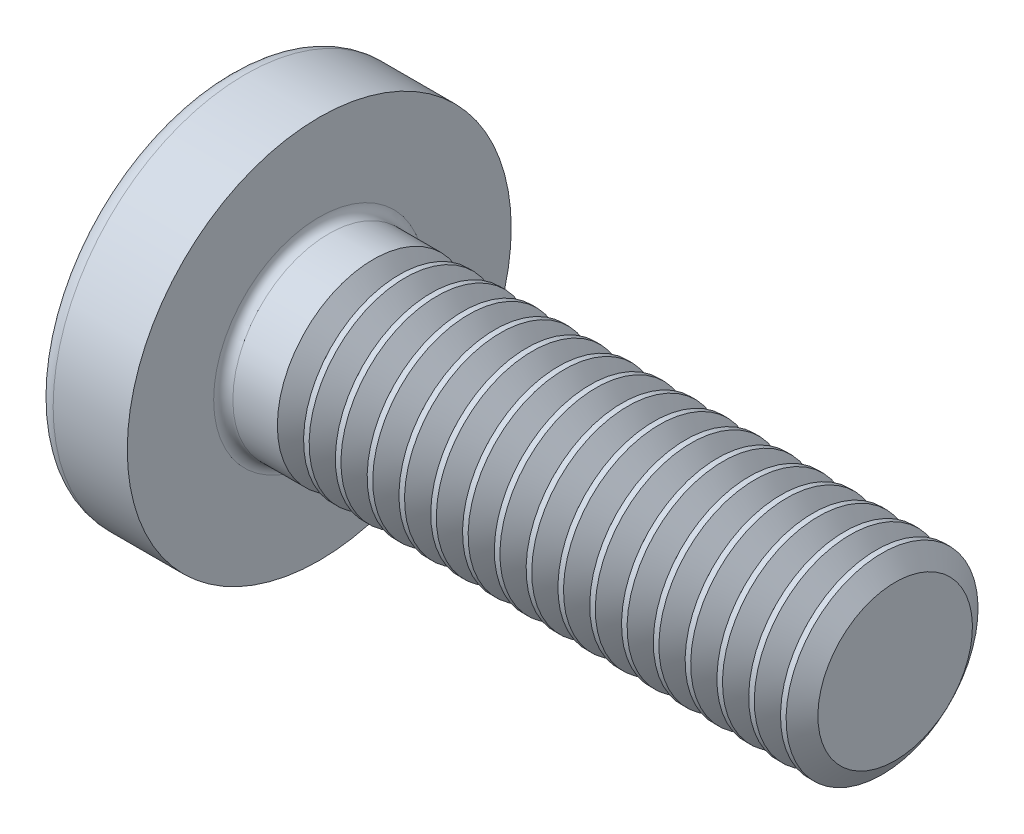
SolidWorks part; units mm, degrees
ref_plane "Plane1" through (0, 0, 0) normal (0, 0, 1) x (1, 0, 0)
ref_plane "Plane2" through (0, 0, 0) normal (0, 1, 0) x (1, 0, 0)
ref_plane "Plane3" through (0, 0, 0) normal (1, 0, 0) x (0, 0, -1)
sketch "BodySke" plane through (0, 0, 0) normal (0, 0, 1) x (1, 0, 0)
  line L0 (3.1, 2) -> (3.1, 4)
  line L1 (3.45, 6.35) -> (3.45, -3.175) construction
  line L2 (-25.4, 0) -> (127, 0) construction
  line L3 (15.1, 0) -> (0, 0)
  line L4 (3.1, 2) -> (15.1, 2)
  line L5 (15.1, 2) -> (15.1, 0)
  line L6 (1.5553, 4) -> (3.1, 4)
  line L8 (3.1, 6.35) -> (3.1, -3.175) construction
  arc A0 (1.2654, 3.8534) -> (0, 0) centre (6.5, 0) ccw
  arc A2 (1.2654, 3.8534) -> (1.5553, 4) centre (1.5553, 3.64) cw
  dimension "Head_crown_rad" = 6.5
  dimension "Head_fillet_rad" = 0.36
  dimension "Length" = 12
  dimension "Head_ht" = 3.1
  dimension "Head_dia" = 8
  dimension "Advance" = 0.7
  dimension "Thread_nom" = 12
  dimension "Diameter" = 4
revolve "Base-Revolve" add sketch "BodySke"
cosmetic thread "ThreadCosmetic" [suppressed]
fillet "Fillet1" radius 0.2 1 edges at (3.1, 0, 2)
sketch "Sketch3" plane through (0, 0, 0) normal (1, 0, 0) x (0, 0, -1)
  line L0 (0.515, -2.15) -> (-0.515, -2.15)
  line L1 (0.515, -2.15) -> (0.515, 2.15)
  line L2 (-0.515, 2.15) -> (0.515, 2.15)
  line L3 (-0.515, 2.15) -> (-0.515, -2.15)
  dimension "Cross_dia" = 4.3
  dimension "D1" = 2.15
  dimension "Cross_width" = 1.03
  dimension "D2" = 0.515
ref_plane "Plane4" through (2.34, 0, 0) normal (1, 0, 0) x (0, 0, -1)
sketch "Sketch4" plane through (2.34, 0, 0) normal (1, 0, 0) x (0, 0, -1)
  line L0 (0.515, -0.9833) -> (-0.515, -0.9833)
  line L1 (0.515, -0.9833) -> (0.515, 0.9833)
  line L2 (-0.515, 0.9833) -> (0.515, 0.9833)
  line L3 (-0.515, 0.9833) -> (-0.515, -0.9833)
  dimension "D1" = 1.03
  dimension "D2" = 1.9666
  dimension "D3" = 0.515
  dimension "D4" = 0.9833
loft "Recess" cut profiles "Sketch3", "Sketch4"
pattern_circular "RecPat" count 2 every 90 about axis through (0, 0, 0) along (1, 0, 0) of "Recess"
sketch "RecCorSke" plane through (0, 0, 0) normal (0, 0, 1) x (1, 0, 0)
  line L0 (-3.175, 0) -> (15.875, 0) construction
  line L1 (-25.4, 0) -> (127, 0) construction
  line L2 (0, 0) -> (0, 1.0146)
  line L3 (0, 1.0146) -> (2.34, 0.851)
  line L4 (2.34, 0.851) -> (2.6165, 0)
  line L5 (2.6165, 0) -> (0, 0)
  dimension "Diameter" = 1.702
  dimension "Depth" = 2.34
  dimension "Draft_angle" = 4
  dimension "Bottom_angle" = 18
revolve "RecessCore" cut sketch "RecCorSke" angle 360 about L0
sketch "ThdSchSke" plane through (0, 0, 0) normal (0, 0, 1) x (1, 0, 0)
  line L0 (4.5, -1.61) -> (4.2269, -2)
  line L1 (4.5, -1.61) -> (4.7731, -2)
  line L2 (4.7731, -2) -> (4.7731, -2.5)
  line L3 (-3.175, 0) -> (5.1513, 0) construction
  line L5 (4.7731, -2.5) -> (4.2269, -2.5)
  line L6 (4.2269, -2.5) -> (4.2269, -2)
  dimension "Diameter" = 4
  dimension "SideAngle" = 55
  dimension "VeeAngle" = 70
  dimension "Thread_minor" = 3.22
  dimension "Overcut" = 5
  dimension "Start" = 4.5
revolve "ThreadSchematic" cut sketch "ThdSchSke" angle 360 about L3
pattern_linear "ThdSchPat" count 17 spacing 0.6625 along (1, 0, 0) of "ThreadSchematic"
equation "\"D1@Sketch3\" = \"Cross_dia@Sketch3\" / 2"
equation "\"D2@Sketch3\" = \"Cross_width@Sketch3\" / 2"
equation "\"Depth@RecCorSke\" = \"Cross_depth@Plane4\""
equation "\"D1@Sketch4\" = \"Cross_width@Sketch3\""
equation "\"D2@Sketch4\" = \"Cross_dia@Sketch3\" - 2.0 * \"Cross_depth@Plane4\" * tan(26.5  * 0.017453292)"
equation "\"D3@Sketch4\" = \"D1@Sketch4\" / 2"
equation "\"D4@Sketch4\" = \"D2@Sketch4\" / 2"
equation "\"Thread_length@ThreadCosmetic\" = ((sgn( (\"Length@BodySke\" - \"Advance@BodySke\" * 2.0 ) - \"Thread_nom@BodySke\" )-1)*( (\"Length@BodySke\" - \"Advance@BodySke\" * 2.0 ) - \"Thread_nom@BodySke\" ))/-2+ \"Thread_nom@BodySke\""
equation "\"Thread_minor@ThdSchSke\" = \"Thread_minor@ThreadCosmetic\""
equation "\"Diameter@ThdSchSke\" = \"Diameter@BodySke\""
equation "\"Overcut@ThdSchSke\" = \"Diameter@BodySke\" * 1.25"
equation "\"Start@ThdSchSke\" = \"Head_ht@BodySke\" + \"Length@BodySke\" - \"Thread_length@ThreadCosmetic\"  '---Non-countersunk---"
equation "\"Num_threads@ThdSchPat\" = int( \"Thread_length@ThreadCosmetic\" / \"Advance@BodySke\" + 0.999 )  + 1"
equation "\"Advance@ThdSchPat\" = \"Thread_length@ThreadCosmetic\" /  (\"Num_threads@ThdSchPat\" - 1) 'relax it"
